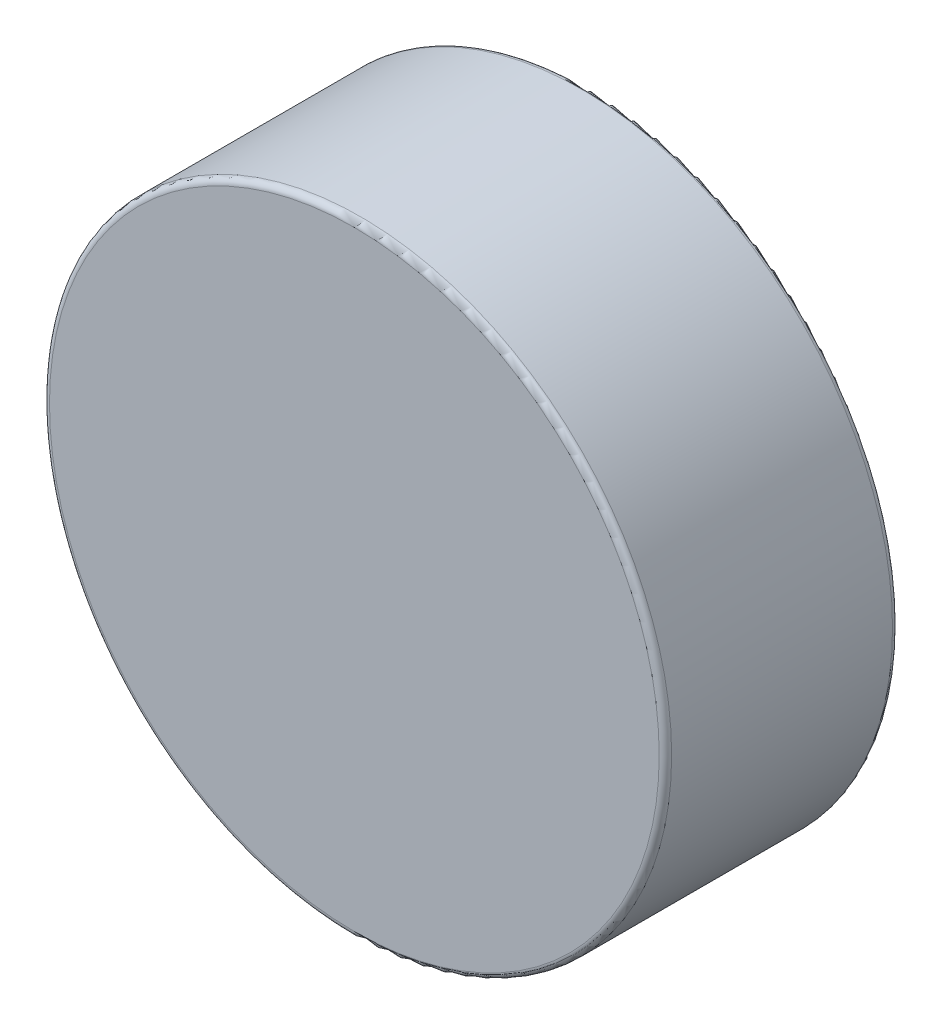
SolidWorks part; units mm, degrees
ref_plane "Front Plane" through (0, 0, 0) normal (0, 0, 1) x (1, 0, 0)
ref_plane "Top Plane" through (0, 0, 0) normal (0, 1, 0) x (1, 0, 0)
ref_plane "Right Plane" through (0, 0, 0) normal (1, 0, 0) x (0, 0, -1)
sketch "Sketch1" plane through (0, 0, 0) normal (0, 0, 1) x (1, 0, 0)
  circle A0 centre (0, 0) radius 6.35 construction
  dimension "OD" = 12.7
sketch "Sketch2" plane through (0, 0, 0) normal (1, 0, 0) x (0, 0, -1)
  line L0 (-2.3813, 0) -> (2.3813, 0) construction
  line L1 (0, 6.35) -> (0, -6.35) construction
  line L3 (-2.3813, 6.35) -> (2.3812, 6.35)
  line L4 (-2.3813, 6.35) -> (-2.3813, -6.35)
  line L5 (-2.3813, -6.35) -> (2.3812, -6.35)
  line L6 (2.3812, 6.35) -> (2.3812, -6.35)
  point P4 (0, 0)
  point P12 (0, 6.35)
  dimension "Thickness" = 4.7625
sketch "Sketch3" plane through (0, 0, 0) normal (0, 0, 1) x (1, 0, 0)
  circle A0 centre (0, 0) radius 6.35 construction
  circle A1 centre (0, 0) radius 6.35
extrude "Boss-Extrude1" add sketch "Sketch3" along normal up to vertex (2.3813 mm away) and the other way up to vertex (2.3813 mm away) up to point (0, 6.35, 2.3813) other way up to point (0, 6.35, -2.3812)
fillet "Fillet1" radius 0.127 2 edges at (6.35, 0, -2.3812) (6.35, 0, 2.3813)
equation "\"Fillet@Fillet1\"=.005"
